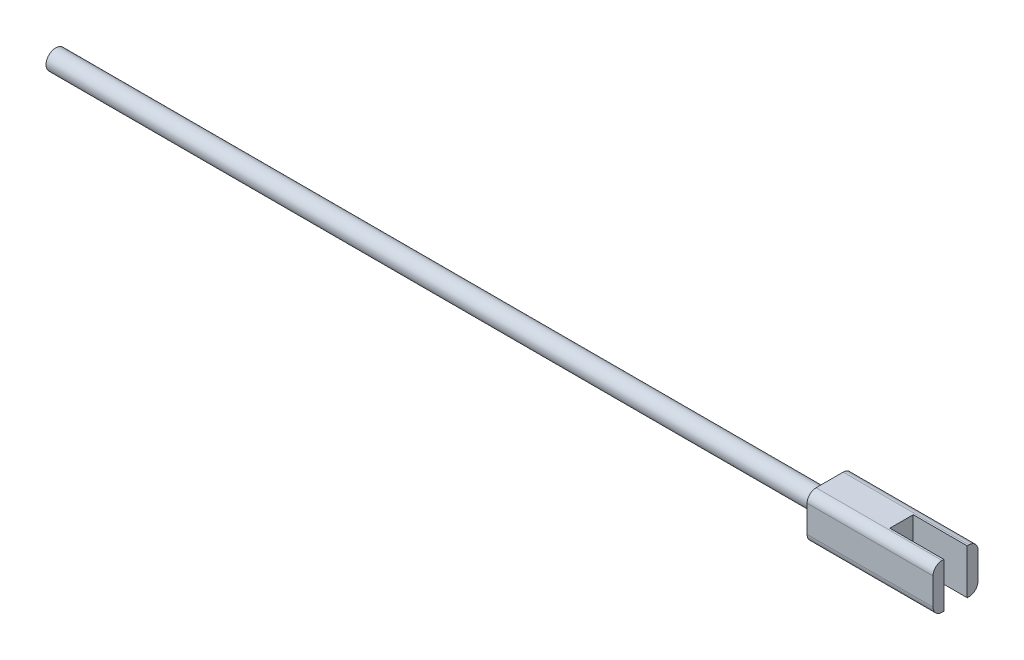
SolidWorks part; units mm, degrees
ref_plane "Front Plane" through (0, 0, 0) normal (0, 0, 1) x (1, 0, 0)
ref_plane "Top Plane" through (0, 0, 0) normal (0, 1, 0) x (1, 0, 0)
ref_plane "Right Plane" through (0, 0, 0) normal (1, 0, 0) x (0, 0, -1)
sketch "Sketch1" plane through (0, 0, 0) normal (1, 0, 0) x (0, 0, -1)
  circle A0 centre (0, 0) radius 1.09
extrude "Boss-Extrude1" add sketch "Sketch1" along normal blind 88.041
ref_plane "Plane1" through (86.041, 0, 0) normal (1, 0, 0) x (0, 0, -1)
sketch "Sketch2" plane through (86.041, 0, 0) normal (1, 0, 0) x (0, 0, -1)
  line L0 (-1.5, -2.5) -> (1.5, -2.5)
  line L1 (2.5, -1.5) -> (2.5, 1.5)
  line L2 (1.5, 2.5) -> (-1.5, 2.5)
  line L3 (-2.5, 1.5) -> (-2.5, -1.5)
  arc A0 (1.5, -2.5) -> (2.5, -1.5) centre (1.5, -1.5) ccw
  arc A1 (2.5, 1.5) -> (1.5, 2.5) centre (1.5, 1.5) ccw
  arc A2 (-1.5, 2.5) -> (-2.5, 1.5) centre (-1.5, 1.5) ccw
  arc A3 (-2.5, -1.5) -> (-1.5, -2.5) centre (-1.5, -1.5) ccw
extrude "Boss-Extrude2" add sketch "Sketch2" along normal blind 14
sketch "Sketch3" plane through (0, 0, 0) normal (0, 1, 0) x (1, 0, 0)
  line L0 (94.041, 1.3) -> (101.041, 1.3)
  line L1 (101.041, 1.3) -> (101.041, -1.3)
  line L2 (101.041, -1.3) -> (94.041, -1.3)
  line L3 (94.041, -1.3) -> (94.041, 1.3)
extrude "Cut-Extrude1" cut sketch "Sketch3" against normal through all and the other way through all
